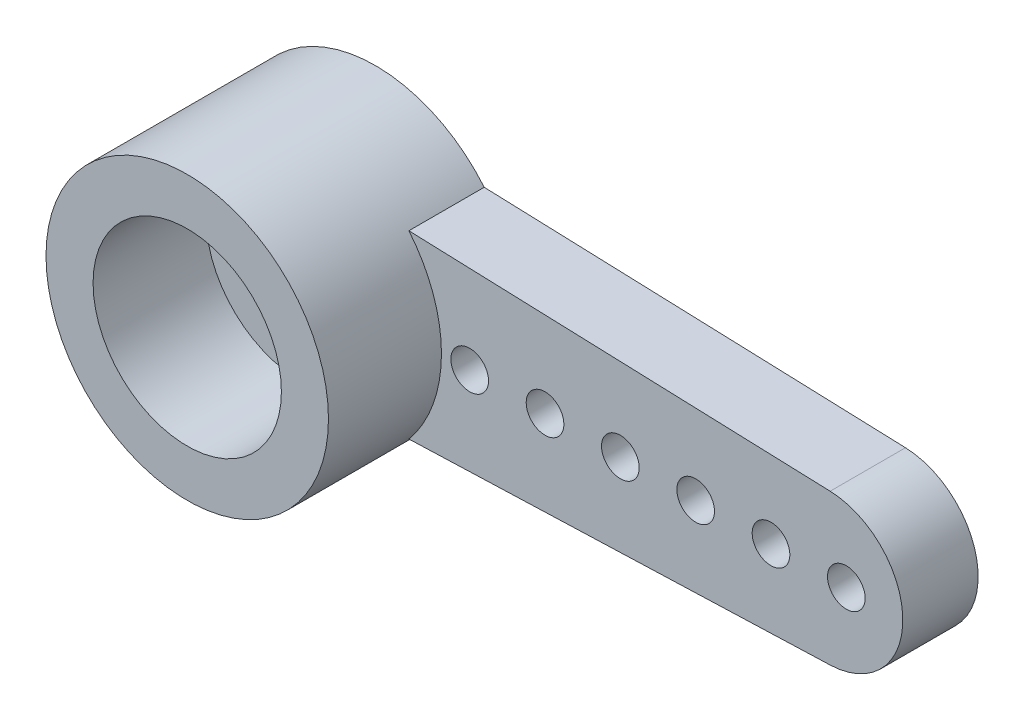
SolidWorks part; units mm, degrees
ref_plane "Спереди" through (0, 0, 0) normal (0, 0, 1) x (1, 0, 0)
ref_plane "Сверху" through (0, 0, 0) normal (0, 1, 0) x (1, 0, 0)
ref_plane "Справа" through (0, 0, 0) normal (1, 0, 0) x (0, 0, -1)
sketch "Эскиз1" plane through (0, 0, 0) normal (0, 0, 1) x (1, 0, 0)
  line L0 (0.2332, -2.4891) -> (0, -2.4974)
  line L1 (-2.8855, 2.3951) -> (0, 2.4974)
  line L2 (-0.2332, -2.4891) -> (0, -2.4974)
  line L4 (14.0708, -1.9987) -> (2.8855, -2.3951)
  line L5 (14.0708, 1.9987) -> (0, 2.4974)
  circle A0 centre (0, 0) radius 3.75
  circle A1 centre (0, 0) radius 2.5
  arc A3 (13.967, -1.9997) -> (14.0708, 1.9987) centre (14, 0) ccw
  point P14 (0, 0)
  dimension "D1" = 7.5
  dimension "D2" = 5
extrude "Бобышка-Вытянуть3" add sketch "Эскиз1" along normal blind 2
sketch "Эскиз2" plane through (0, 0, 2) normal (0, 0, 1) x (1, 0, 0)
  circle A0 centre (0, 0) radius 3.75
  circle A1 centre (0, 0) radius 2.5
  dimension "D1" = 5
extrude "Бобышка-Вытянуть5" add sketch "Эскиз2" along normal blind 3 separate body
sketch "Эскиз4" plane through (0, 0, 0) normal (0, 0, -1) x (-1, 0, 0)
  line L0 (-16, 0) -> (-14.5, 0)
  line L1 (-14.5, 0) -> (-12.5, 0)
  line L2 (-12.5, 0) -> (-10.5, 0)
  line L3 (-10.5, 0) -> (-8.5, 0)
  line L4 (-8.5, 0) -> (-6.5, 0)
  line L5 (-6.5, 0) -> (-4.5, 0)
  arc A0 (-14.0708, 1.9987) -> (-14.0708, -1.9987) centre (-14, 0) ccw construction
  circle A1 centre (-14.5, 0) radius 0.5
  circle A2 centre (-12.5, 0) radius 0.5
  circle A3 centre (-10.5, 0) radius 0.5
  circle A4 centre (-8.5, 0) radius 0.5
  circle A5 centre (-6.5, 0) radius 0.5
  circle A6 centre (-4.5, 0) radius 0.5
  circle A7 centre (4.5, 0) radius 0.5
  circle A8 centre (6.5, 0) radius 0.5
  circle A9 centre (8.5, 0) radius 0.5
  circle A10 centre (10.5, 0) radius 0.5
  circle A11 centre (12.5, 0) radius 0.5
  circle A12 centre (14.5, 0) radius 0.5
  dimension "D2" = 1
  dimension "D8" = 1
  dimension "D9" = 1
  dimension "D10" = 1
  dimension "D11" = 1
  dimension "D12" = 1
  dimension "D1" = 1.5
  dimension "D3" = 2
  dimension "D4" = 2
  dimension "D5" = 2
  dimension "D6" = 2
  dimension "D7" = 2
extrude "Вырез-Вытянуть1" cut sketch "Эскиз4" against normal blind 2
sketch "Эскиз5" plane through (0, 0, 0) normal (0, 0, -1) x (-1, 0, 0)
  circle A0 centre (0, 0) radius 2.5
extrude "Бобышка-Вытянуть7" add sketch "Эскиз5" against normal blind 1
sketch "Эскиз6" plane through (0, 0, 0) normal (0, 0, -1) x (-1, 0, 0)
  circle A0 centre (0, 0) radius 2.5
  dimension "D1" = 5
sketch "草图1" plane through (0, 0, 2) normal (0, 0, -1) x (-1, 0, 0)
  circle A0 centre (0, 0) radius 3.75
extrude "凸台-拉伸1" add sketch "草图1" along normal up to surface (2 mm away) up to face at (-2.5, 0, 0)
